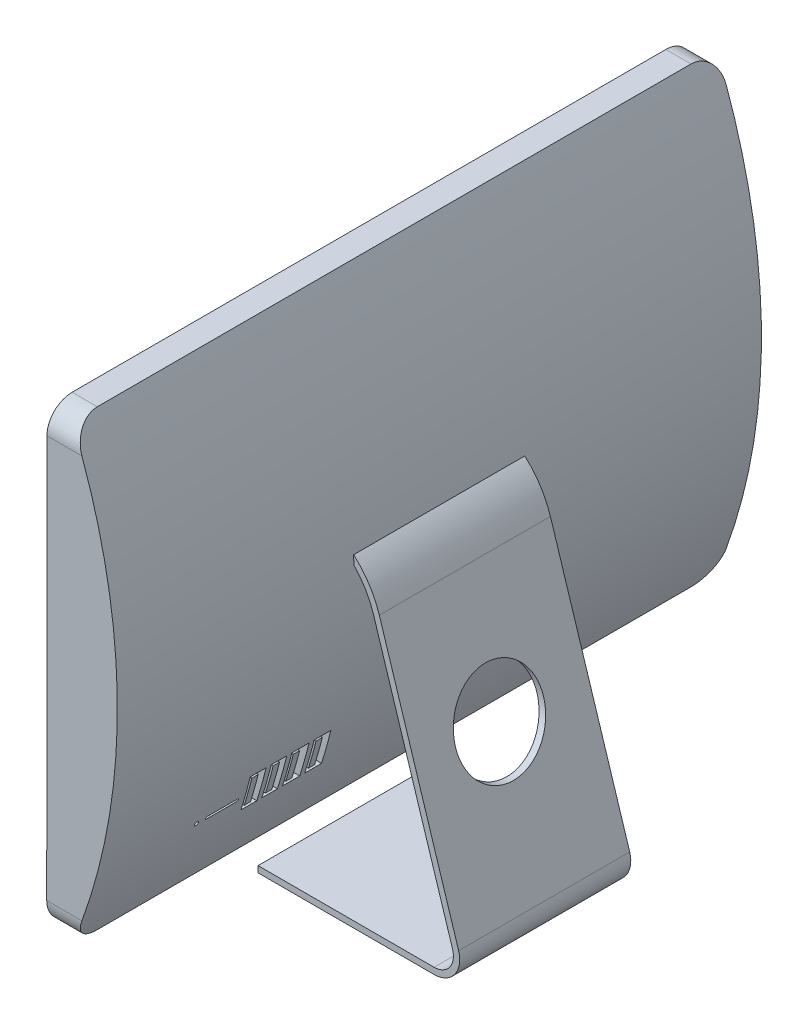
SolidWorks part; units mm, degrees
material "Plain Carbon Steel"
ref_plane "Front Plane" through (0, 0, 0) normal (0, 0, 1) x (1, 0, 0)
ref_plane "Top Plane" through (0, 0, 0) normal (0, 1, 0) x (1, 0, 0)
ref_plane "Right Plane" through (0, 0, 0) normal (1, 0, 0) x (0, 0, -1)
sketch "Sketch1" plane through (0, 0, 0) normal (0, 0, 1) x (1, 0, 0)
  line L1 (0, 0) -> (25.4, 0)
  line L2 (0, 0) -> (0, 457.2)
  line L3 (0, 457.2) -> (25.4, 457.2)
  arc A2 (25.4, 0) -> (25.4, 457.2) centre (-524.0001, 228.6) ccw
  dimension "D3" = 595.0617
  dimension "D1" = 457.2
  dimension "D2" = 25.4
extrude "Boss-Extrude1" add sketch "Sketch1" along normal blind 650.24
fillet "Fillet1" radius 25.4 4 edges at (12.7, 0, 650.24) (12.7, 0, 0) (12.7, 457.2, 0) (12.7, 457.2, 650.24)
sketch "Sketch2" plane through (0, 0, 0) normal (-1, 0, 0) x (0, 0, 1)
  line L0 (0, 431.8) -> (0, 25.4) construction
  line L1 (650.24, 431.8) -> (650.24, 25.4) construction
  line L2 (624.84, 0) -> (25.4, 0) construction
  line L3 (0, 69.4409) -> (0, 25.4)
  line L4 (650.24, 69.4409) -> (650.24, 25.4)
  line L5 (624.84, 0) -> (25.4, 0)
  line L6 (0, 69.4409) -> (650.24, 69.4409)
  arc A0 (624.84, 0) -> (650.24, 25.4) centre (624.84, 25.4) ccw construction
  arc A1 (0, 25.4) -> (25.4, 0) centre (25.4, 25.4) ccw construction
  arc A2 (624.84, 0) -> (650.24, 25.4) centre (624.84, 25.4) ccw
  arc A3 (0, 25.4) -> (25.4, 0) centre (25.4, 25.4) ccw
  dimension "D1" = 69.4409
extrude "Boss-Extrude2" add sketch "Sketch2" along normal blind 0.254
sketch "Sketch4" plane through (0, 0, 0) normal (-1, 0, 0) x (0, 0, 1)
  line L2 (624.84, 431.8) -> (25.4, 98.6434) construction
  line L7 (624.84, 457.2) -> (25.4, 457.2) construction
  line L8 (25.4, 98.6434) -> (624.84, 98.6434)
  line L9 (25.4, 98.6434) -> (25.4, 431.8)
  line L10 (25.4, 431.8) -> (624.84, 431.8)
  line L11 (624.84, 98.6434) -> (624.84, 431.8)
  dimension "D3" = 101.8611
  dimension "D2" = 685.8
  dimension "D1" = 25.4
  dimension "D4" = 624.84
extrude "Boss-Extrude3" add sketch "Sketch4" along normal blind 0.0025
ref_plane "Plane1" through (0, 0, 325.12) normal (0, 0, 1) x (1, 0, 0)
sketch "Sketch5" plane through (0, 0, 325.12) normal (0, 0, 1) x (1, 0, 0)
  line L0 (170.7672, -51.1987) -> (90.7344, 202.071)
  line L1 (-25.705, -76.2) -> (152.095, -76.2)
  line L2 (-25.705, -82.55) -> (152.095, -82.55)
  line L3 (0, 457.2) -> (25.4, 457.2) construction
  line L4 (176.8384, -49.3367) -> (96.7893, 203.9843)
  line L5 (-25.705, -76.2) -> (-25.705, -82.55)
  line L11 (0, 431.8) -> (0, 69.4409)
  line L12 (0, 69.4409) -> (-0.254, 69.4409)
  line L13 (-0.254, 69.4409) -> (-0.254, 25.4)
  line L14 (-0.254, 25.4) -> (35.2925, 25.4)
  line L15 (35.2925, 431.8) -> (0, 431.8)
  line L17 (0, 69.4409) -> (-0.254, 69.4409)
  arc A0 (90.7344, 202.071) -> (71.0274, 234.9793) centre (11.6991, 177.096) ccw
  arc A1 (170.7672, -51.1987) -> (152.095, -76.2) centre (152.095, -56.7267) cw
  arc A6 (176.8384, -49.3367) -> (152.095, -82.55) centre (152.095, -56.7267) cw
  arc A7 (96.7893, 203.9843) -> (70.8649, 243.8997) centre (11.6991, 177.096) ccw
  arc A8 (96.7893, 203.9843) -> (15.1994, 266.2648) centre (11.6991, 177.096) ccw construction
  arc A10 (35.2925, 25.4) -> (35.2925, 431.8) centre (-524.0001, 228.6) ccw
  arc A12 (90.7344, 202.071) -> (14.9504, 259.9197) centre (11.6991, 177.096) ccw construction
  arc A13 (35.2925, 25.4) -> (35.2925, 431.8) centre (-524.0001, 228.6) ccw construction
  arc A14 (71.0274, 234.9793) -> (70.8649, 243.8997) centre (-524.0001, 228.6) ccw
  point P28 (0, 0)
  dimension "D2" = 19.4733
  dimension "D9" = 278.271
  dimension "D1" = 177.8
  dimension "D3" = 31.2044
  dimension "D4" = 196.4722
  dimension "D5" = 533.4
  dimension "D6" = 25.9244
  dimension "D7" = 265.614
  dimension "D8" = 71.0274
  dimension "D10" = 6.35
  dimension "D11" = 0
extrude "Boss-Extrude4" add sketch "Sketch5" along normal mid plane 172.72 contours L0 A0 A14 A7 L4 A6 L2 L5 L1 A1
ref_plane "Plane2" through (200.66, 0, 0) normal (1, 0, 0) x (0, 0, -1)
sketch "Sketch6" plane through (200.66, 0, 0) normal (1, 0, 0) x (0, 0, -1)
  circle A0 centre (-327.1039, 87.1894) radius 44.45
  point P2 (0, 0)
  dimension "D1" = 88.9
  dimension "D2" = 327.1039
  dimension "D3" = 87.1894
extrude "Cut-Extrude1" cut sketch "Sketch6" against normal blind 99.568
sketch "Sketch7" plane through (200.66, 0, 0) normal (1, 0, 0) x (0, 0, -1)
  line L0 (-438.8968, 50.6347) -> (-456.328, 50.6347)
  line L1 (-416.9139, 50.6347) -> (-433.8168, 50.6347)
  line L2 (-416.9139, 50.6347) -> (-416.9139, 84.2723)
  line L3 (-416.9139, 84.2723) -> (-433.8168, 84.2723)
  line L4 (-433.8168, 50.6347) -> (-433.8168, 84.2723)
  line L5 (-438.8968, 50.6347) -> (-438.8968, 84.2723)
  line L6 (-438.8968, 84.2723) -> (-456.328, 84.2723)
  line L7 (-456.328, 50.6347) -> (-456.328, 84.2723)
  line L8 (-461.408, 50.6347) -> (-477.1392, 50.6347)
  line L9 (-461.408, 50.6347) -> (-461.408, 84.2723)
  line L10 (-461.408, 84.2723) -> (-477.1392, 84.2723)
  line L11 (-477.1392, 50.6347) -> (-477.1392, 84.2723)
  line L12 (-482.2192, 50.6347) -> (-498.2736, 50.6347)
  line L13 (-482.2192, 50.6347) -> (-482.2192, 84.2723)
  line L14 (-482.2192, 84.2723) -> (-498.2736, 84.2723)
  line L15 (-498.2736, 50.6347) -> (-498.2736, 84.2723)
  line L16 (-537.2746, 65.3723) -> (-506.4227, 65.3723) construction
  line L17 (-495.9845, 81.7002) -> (-489.6345, 81.7002)
  line L18 (-495.9845, 81.7002) -> (-495.9845, 53.9926)
  line L19 (-495.9845, 53.9926) -> (-489.6345, 53.9926)
  line L20 (-489.6345, 81.7002) -> (-489.6345, 53.9926)
  line L21 (-474.4497, 81.7002) -> (-468.0997, 81.7002)
  line L22 (-474.4497, 81.7002) -> (-474.4497, 53.9926)
  line L23 (-474.4497, 53.9926) -> (-468.0997, 53.9926)
  line L24 (-468.0997, 81.7002) -> (-468.0997, 53.9926)
  line L25 (-454.1628, 81.7002) -> (-447.8128, 81.7002)
  line L26 (-454.1628, 81.7002) -> (-454.1628, 53.9926)
  line L27 (-454.1628, 53.9926) -> (-447.8128, 53.9926)
  line L28 (-447.8128, 81.7002) -> (-447.8128, 53.9926)
  line L29 (-431.2369, 81.7002) -> (-424.8869, 81.7002)
  line L30 (-431.2369, 81.7002) -> (-431.2369, 53.9926)
  line L31 (-431.2369, 53.9926) -> (-424.8869, 53.9926)
  line L32 (-424.8869, 81.7002) -> (-424.8869, 53.9926)
  line L33 (-537.2746, 66.6423) -> (-506.4227, 66.6423)
  line L34 (-537.2746, 64.1023) -> (-506.4227, 64.1023)
  arc A0 (-537.2746, 66.6423) -> (-537.2746, 64.1023) centre (-537.2746, 65.3723) ccw
  arc A1 (-506.4227, 64.1023) -> (-506.4227, 66.6423) centre (-506.4227, 65.3723) ccw
  circle A2 centre (-547.4984, 65.3723) radius 1.896
  point P34 (-521.8487, 65.3723)
  point P41 (-547.4984, 65.3723)
  dimension "D1" = 5.08
  dimension "D2" = 5.08
  dimension "D3" = 5.08
  dimension "D4" = 33.6376
  dimension "D5" = 16.0543
  dimension "D6" = 6.35
  dimension "D7" = 30.8518
  dimension "D8" = 2.54
extrude "Cut-Extrude2" cut sketch "Sketch7" against normal blind 173.228
